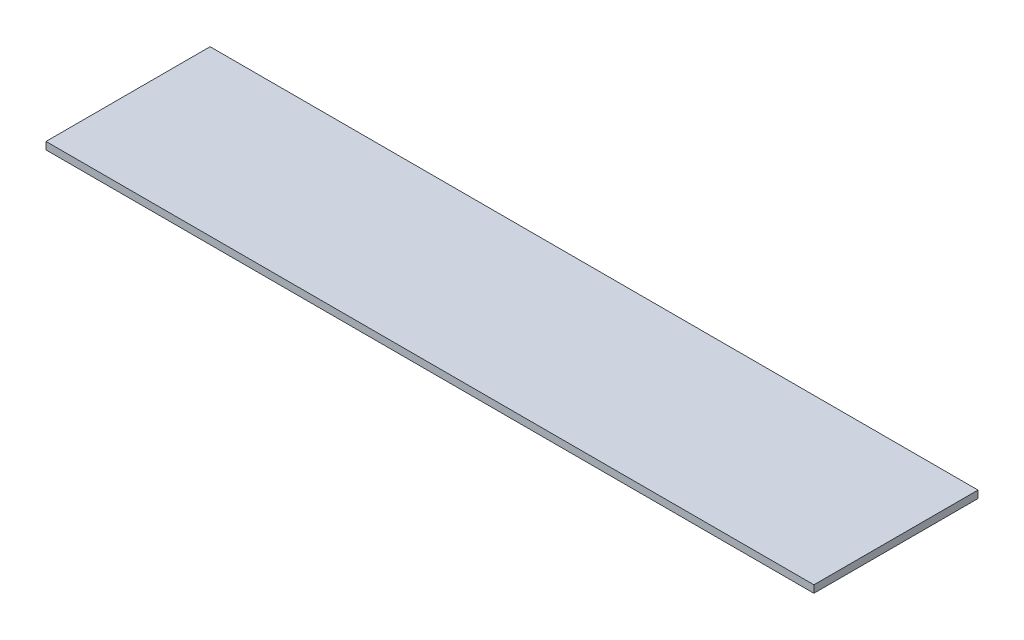
SolidWorks part; units mm, degrees
ref_plane "前视基准面" through (0, 0, 0) normal (0, 0, 1) x (1, 0, 0)
ref_plane "上视基准面" through (0, 0, 0) normal (0, 1, 0) x (1, 0, 0)
ref_plane "右视基准面" through (0, 0, 0) normal (1, 0, 0) x (0, 0, -1)
sketch "草图1" plane through (0, 0, 0) normal (0, 1, 0) x (1, 0, 0)
  line L1 (-462.8732, 231.4366) -> (1409.1268, 231.4366)
  line L2 (-462.8732, 231.4366) -> (-462.8732, -168.5634)
  line L3 (-462.8732, -168.5634) -> (1409.1268, -168.5634)
  line L4 (1409.1268, 231.4366) -> (1409.1268, -168.5634)
  dimension "D1" = 1872
  dimension "D2" = 400
extrude "凸台-拉伸1" add sketch "草图1" along normal blind 18
